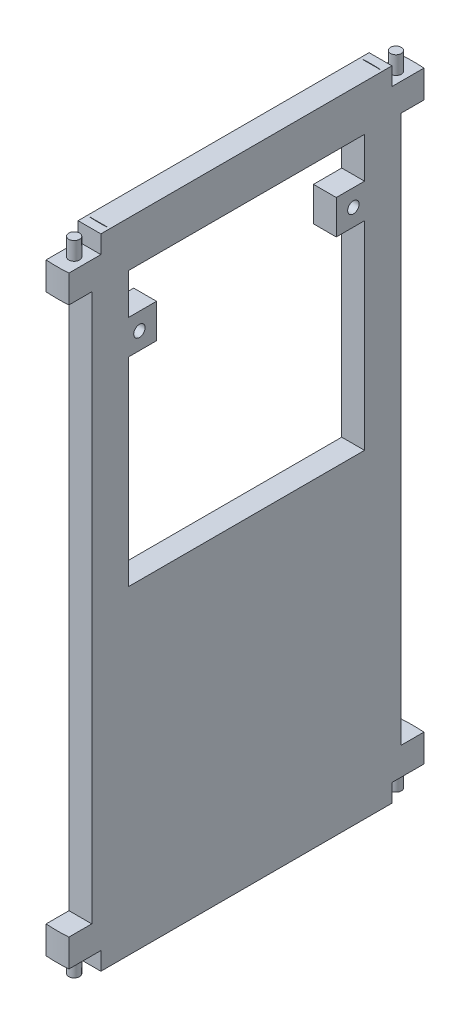
SolidWorks part; units mm, degrees
ref_plane "Front Plane" through (0, 0, 0) normal (0, 0, 1) x (1, 0, 0)
ref_plane "Top Plane" through (0, 0, 0) normal (0, 1, 0) x (1, 0, 0)
ref_plane "Right Plane" through (0, 0, 0) normal (1, 0, 0) x (0, 0, -1)
sketch "Sketch1" plane through (0, 0, 0) normal (0, 1, 0) x (1, 0, 0)
  line L0 (-3.175, -37.9675) -> (-3.175, 37.9675)
  line L3 (3.175, -37.9675) -> (3.175, 37.9675)
  line L4 (-3.164, -37.9684) -> (3.175, 38.1) construction
  line L5 (-3.164, 37.9684) -> (3.164, -37.9684) construction
  circle A0 centre (0, 0) radius 49.53
  circle A1 centre (0, 0) radius 38.1
  dimension "D1" = 99.06
  dimension "D2" = 76.2
  dimension "D3" = 6.35
extrude "Boss-Extrude1" add sketch "Sketch1" along normal blind 12.7 contours A0 A1 | L3 A1 L0
sketch "Sketch4" plane through (0, 12.7, 0) normal (0, 1, 0) x (1, 0, 0)
  line L4 (-3.175, -43.05) -> (-3.175, 43.05)
  line L5 (-3.175, -43.05) -> (3.175, -43.05)
  line L6 (-3.175, 43.05) -> (3.175, 43.05)
  line L7 (3.175, -43.05) -> (3.175, 43.05)
  line L8 (-3.175, -43.05) -> (3.175, 43.05) construction
  line L9 (-3.175, 43.05) -> (3.175, -43.05) construction
  line L11 (3.175, -32.89) -> (-3.175, -32.89)
  line L12 (3.175, -32.89) -> (3.175, 32.89)
  line L13 (3.175, 32.89) -> (-3.175, 32.89)
  line L14 (-3.175, -32.89) -> (-3.175, 32.89)
  point P1 (0, 0)
  line M8 (3.175, -37.9675) -> (3.175, 37.9675)
  line M10 (-3.175, 37.9675) -> (-3.175, -37.9675)
  dimension "D1" = 86.1
  dimension "D2" = 6.35
  dimension "D3" = 10.16
  dimension "D4" = 10.16
extrude "Boss-Extrude4" add sketch "Sketch4" along normal blind 152.4 contours L11 L4 L5 M8 | L13 L6 M8 M10
sketch "Sketch6" plane through (0, 165.1, 0) normal (0, 1, 0) x (1, 0, 0)
  line L0 (-3.175, -32.89) -> (-3.175, -43.05) construction
  line L2 (-3.175, -37.97) -> (3.175, -37.97)
  line L3 (-3.175, -37.97) -> (-3.175, 37.97)
  line L5 (-3.175, 37.97) -> (3.175, 37.97)
  line L6 (3.175, -37.97) -> (3.175, 37.97)
  line L7 (3.175, 32.89) -> (3.175, 43.05) construction
  circle A2 centre (0, 0) radius 38.1
  circle A3 centre (0, 0) radius 49.53
  line M3 (3.175, -43.05) -> (3.175, -32.89)
  line M4 (3.175, -32.89) -> (-3.175, -32.89)
  line M5 (-3.175, -32.89) -> (-3.175, -43.05)
  line M6 (-3.175, -43.05) -> (3.175, -43.05)
  dimension "D1" = 76.2
  dimension "D2" = 99.06
extrude "Boss-Extrude8" add sketch "Sketch6" along normal blind 12.7 contours A3 A2 L3 L5 L6 M3 M6 M5 | L6 A2 L5 L3 M4 | L2 A2 L6 M4 M5 | A2 L2 M5 M6 M3
sketch "Sketch7" plane through (0, 0, 0) normal (0, -1, 0) x (1, 0, 0)
  line L0 (-37.774, -4.973) -> (-49.1063, -6.465)
  line L1 (54.483, 0) -> (-54.483, 0) construction
  line L2 (-37.774, 4.973) -> (-49.1063, 6.465)
  line L3 (0, -54.483) -> (0, 54.483) construction
  line L4 (37.774, 4.973) -> (49.1063, 6.465)
  line L5 (37.774, -4.973) -> (49.1063, -6.465)
  arc A0 (-49.1063, 6.465) -> (-49.1063, -6.465) centre (0, 0) ccw
  arc A2 (-37.774, 4.973) -> (-37.774, -4.973) centre (0, 0) ccw
  arc A4 (37.774, 4.973) -> (37.774, -4.973) centre (0, 0) cw
  arc A5 (49.1063, 6.465) -> (49.1063, -6.465) centre (0, 0) cw
  arc M1 (-6.5314, -40.1117) -> (-6.5314, 40.1117) centre (0, 0) cw
  arc M8 (6.5314, 40.1117) -> (6.5314, -40.1117) centre (0, 0) cw
  circle M9 centre (0, 0) radius 49.53
extrude "Cut-Extrude1" cut sketch "Sketch7" against normal through all and the other way through all contours L2 L0 M1 M9 | L5 L4 M8 M9 | L4 A4 L5 M8 | A2 L2 L0 M1
sketch "Sketch8" plane through (0, 0, -32.89) normal (0, 0, 1) x (1, 0, 0)
  line L0 (3.175, 165.1) -> (3.175, 12.7) construction
  line L1 (3.175, 24.003) -> (-3.175, 24.003)
  line L2 (3.175, 24.003) -> (3.175, 33.528)
  line L3 (3.175, 33.528) -> (-3.175, 33.528)
  line L4 (-3.175, 24.003) -> (-3.175, 33.528)
  line L5 (-3.175, 165.1) -> (-3.175, 12.7) construction
  line L6 (3.175, 12.7) -> (-3.175, 12.7) construction
  line L7 (-3.175, 144.272) -> (3.175, 144.272)
  line L8 (-3.175, 144.272) -> (-3.175, 153.797)
  line L9 (-3.175, 153.797) -> (3.175, 153.797)
  line L10 (3.175, 144.272) -> (3.175, 153.797)
  point P14 (0, 12.7)
  dimension "D1" = 11.303
  dimension "D2" = 9.525
  dimension "D3" = 9.525
  dimension "D4" = 11.303
extrude "Boss-Extrude9" add sketch "Sketch8" along normal blind 7.874
ref_plane "Plane1" through (0, 0, 0.003) normal (0, 0, 1) x (1, 0, 0)
mirror "Mirror1" about plane through (0, 0, 0.003) normal (0, 0, 1) of "Boss-Extrude9"
sketch "Sketch9" plane through (3.175, 0, 0) normal (1, 0, 0) x (0, 0, -1)
  line L0 (25.016, 24.003) -> (25.016, 33.528) construction
  line L2 (25.016, 33.528) -> (32.89, 33.528) construction
  line L3 (25.016, 153.797) -> (32.89, 153.797) construction
  line L4 (25.016, 144.272) -> (25.016, 153.797) construction
  circle A0 centre (29.7785, 28.7655) radius 1.5875
  circle A1 centre (29.7785, 149.0345) radius 1.5875
  dimension "D1" = 3.175
  dimension "D4" = 3.175
  dimension "D2" = 4.7625
  dimension "D3" = 4.7625
  dimension "D5" = 4.7625
  dimension "D6" = 4.7625
extrude "Cut-Extrude2" cut sketch "Sketch9" against normal through all
mirror "Mirror2" about plane through (0, 0, 0.003) normal (0, 0, 1) of "Cut-Extrude2"
sketch "Sketch10" plane through (-3.175, 0, 0) normal (-1, 0, 0) x (0, 0, 1)
  line L1 (-90.5991, 201.8195) -> (92.3854, 201.8195)
  line L2 (-90.5991, 201.8195) -> (-90.5991, -10.2822)
  line L3 (-90.5991, -10.2822) -> (92.3854, -10.2822)
  line L4 (92.3854, 201.8195) -> (92.3854, -10.2822)
extrude "Cut-Extrude3" cut sketch "Sketch10" along normal through all
sketch "Sketch13" plane through (3.175, 0, 0) normal (1, 0, 0) x (0, 0, -1)
  line L2 (67.239, -7.9912) -> (-60.7777, -7.9912)
  line L3 (67.239, -7.9912) -> (67.239, 202.0278)
  line L4 (67.239, 202.0278) -> (-60.7777, 202.0278)
  line L5 (-60.7777, -7.9912) -> (-60.7777, 202.0278)
extrude "Cut-Extrude4" cut sketch "Sketch13" along normal through all
sketch "Sketch14" plane through (0, 177.8, 0) normal (0, 1, 0) x (1, 0, 0)
  line L0 (-3.175, -49.4281) -> (-3.175, 49.4281) construction
  line L1 (-3.175, 40.51) -> (3.175, 40.51)
  line L2 (-3.175, 40.51) -> (-3.175, 49.4281)
  line L3 (-3.175, 49.4281) -> (3.175, 49.4281)
  line L4 (3.175, 40.51) -> (3.175, 49.4281)
  line L5 (-3.1447, 37.97) -> (3.1447, 37.97) construction
  circle A0 centre (0.0152, 44.7881) radius 1.5
  point P8 (-3.175, 40.6775)
  point P11 (-3.175, 49.4281)
  point P12 (3.0883, 51.0733)
  point P13 (3.3062, 50.8982)
  point P16 (2.759, 48.9009)
  point P17 (3.175, 49.4281)
  dimension "D2" = 3
  dimension "D1" = 4.64
  dimension "D3" = 2.54
extrude "Cut-Extrude5" cut sketch "Sketch14" against normal blind 5
sketch "Sketch15" plane through (0, 172.8, 0) normal (0, 1, 0) x (1, 0, 0)
  line L1 (4.6212, 46.8931) -> (-4.2987, 46.8931)
  line L2 (4.6212, 46.8931) -> (4.6212, 52.0966)
  line L3 (4.6212, 52.0966) -> (-4.2987, 52.0966)
  line L4 (-4.2987, 46.8931) -> (-4.2987, 52.0966)
extrude "Cut-Extrude6" cut sketch "Sketch15" along normal blind 5
mirror "Mirror3" about plane through (0, 0, 0.003) normal (0, 0, 1) of "Cut-Extrude5", "Cut-Extrude6"
ref_plane "Plane2" through (0, 88.9, 0) normal (0, -1, 0) x (-1, 0, 0)
mirror "Mirror4" about plane through (0, 88.9, 0) normal (0, -1, 0) of "Mirror3", "Cut-Extrude5", "Cut-Extrude6"
sketch "Sketch16" plane through (0, 12.7, 0) normal (0, 1, 0) x (1, 0, 0)
  line L1 (-3.175, -32.89) -> (3.175, -32.89)
  line L2 (-3.175, -32.89) -> (-3.175, 32.89)
  line L3 (-3.175, 32.89) -> (3.175, 32.89)
  line L4 (3.175, -32.89) -> (3.175, 32.89)
extrude "Boss-Extrude10" add sketch "Sketch16" along normal blind 76.2
